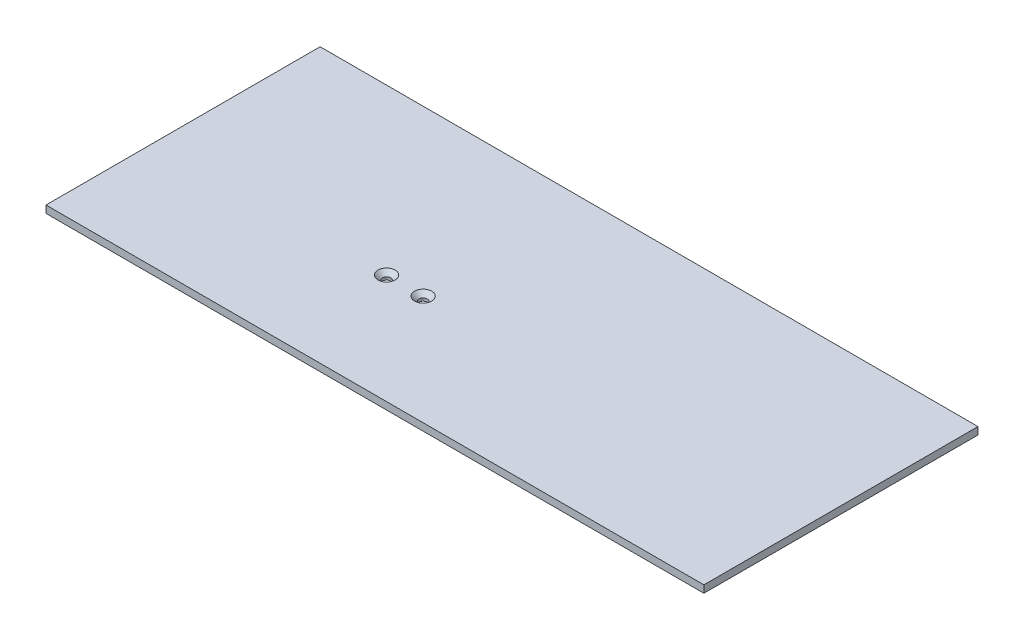
SolidWorks part; units mm, degrees
ref_plane "Front Plane" through (0, 0, 0) normal (0, 0, 1) x (1, 0, 0)
ref_plane "Top Plane" through (0, 0, 0) normal (0, 1, 0) x (1, 0, 0)
ref_plane "Right Plane" through (0, 0, 0) normal (1, 0, 0) x (0, 0, -1)
sketch "Sketch1" plane through (0, 0, 0) normal (0, 1, 0) x (1, 0, 0)
  line L1 (-180, -45) -> (180, -45)
  line L2 (-180, -45) -> (-180, 45)
  line L3 (-180, 45) -> (180, 45) construction
  line L4 (180, -45) -> (180, 45)
  line L5 (-180, -45) -> (180, 45) construction
  line L6 (-180, 45) -> (180, -45) construction
  line L7 (-180, 45) -> (180, 45) construction
  line L8 (-180, 45) -> (-180, 105)
  line L9 (-180, 105) -> (180, 105)
  line L10 (180, 45) -> (180, 105)
  point P0 (0, 0)
  dimension "D1" = 360
  dimension "D2" = 90
  dimension "D3" = 60
extrude "Boss-Extrude1" add sketch "Sketch1" along normal blind 4
hole_wizard "CSK for M4 Countersunk Flat Head Screw1" positions "Sketch3" profile "Sketch4" countersink size "M4" standard "ISO" end condition through all
sketch "Sketch3" plane through (0, 4, 0) normal (0, 1, 0) x (1, 0, 0)
  line L0 (-153.6348, -45) -> (-153.6348, 0) construction
  line L1 (-55, 0) -> (55, 0) construction
  line L3 (-180, -45) -> (180, -45) construction
  point P0 (-53.6348, 15)
  point P2 (-33.6348, 15)
  dimension "D1" = 20
  dimension "D2" = 100
  dimension "D3" = 60
sketch "Sketch4" plane through (-53.6348, 4, -15) normal (1, 0, 0) x (0, 0, 1)
  line L0 (0, 0) -> (0, 4)
  line L1 (0, 4) -> (2.25, 4)
  line L2 (2.25, 4) -> (2.25, 2.45)
  line L3 (2.25, 2.45) -> (4.7, 0)
  line L5 (4.7, 0) -> (0, 0)
  line L6 (-2.25, 2.45) -> (-4.7, 0) construction
  line L11 (0, -6.35) -> (0, 107.95) construction
  dimension "Thru Hole Dia." = 4.5
  dimension "Thru Hole Depth" = 4
  dimension "Near C'Sink Dia." = 9.4
  dimension "Near C'Sink Angle" = 90
